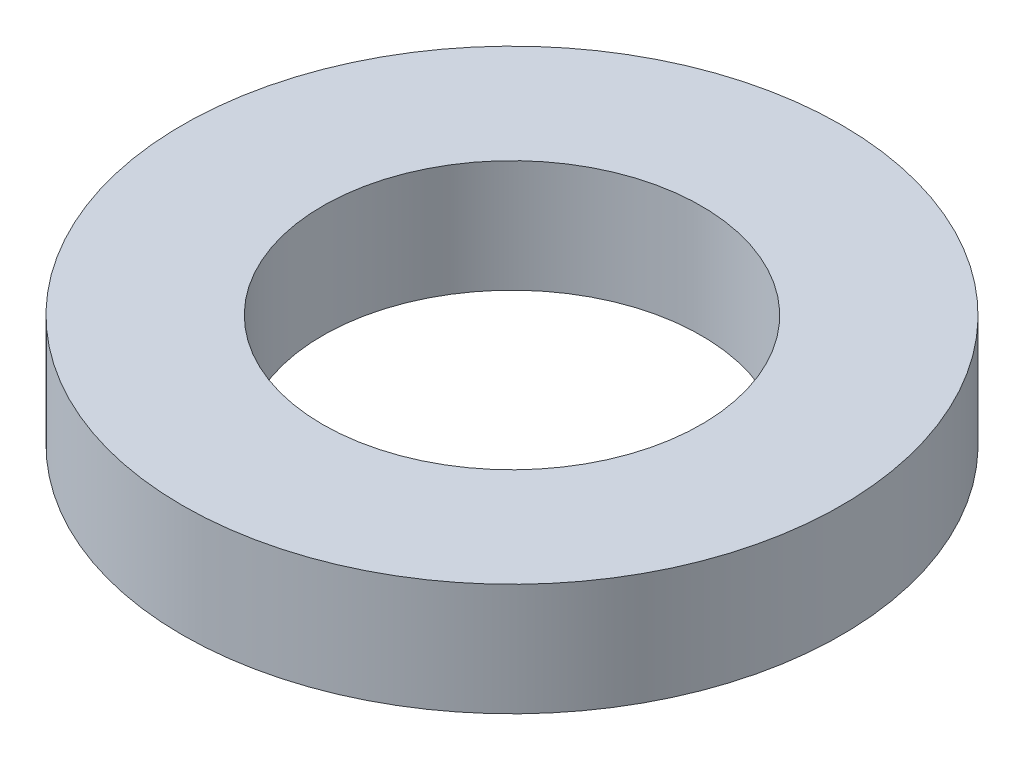
SolidWorks part; units mm, degrees
ref_plane "前视基准面" through (0, 0, 0) normal (0, 0, 1) x (1, 0, 0)
ref_plane "上视基准面" through (0, 0, 0) normal (0, 1, 0) x (1, 0, 0)
ref_plane "右视基准面" through (0, 0, 0) normal (1, 0, 0) x (0, 0, -1)
sketch "草图1" plane through (0, 0, 0) normal (0, 1, 0) x (1, 0, 0)
  circle A0 centre (0, 0) radius 11.75
  circle A1 centre (0, 0) radius 6.75
  dimension "D1" = 13.5
  dimension "D2" = 5
extrude "凸台-拉伸1" add sketch "草图1" along normal mid plane 4
